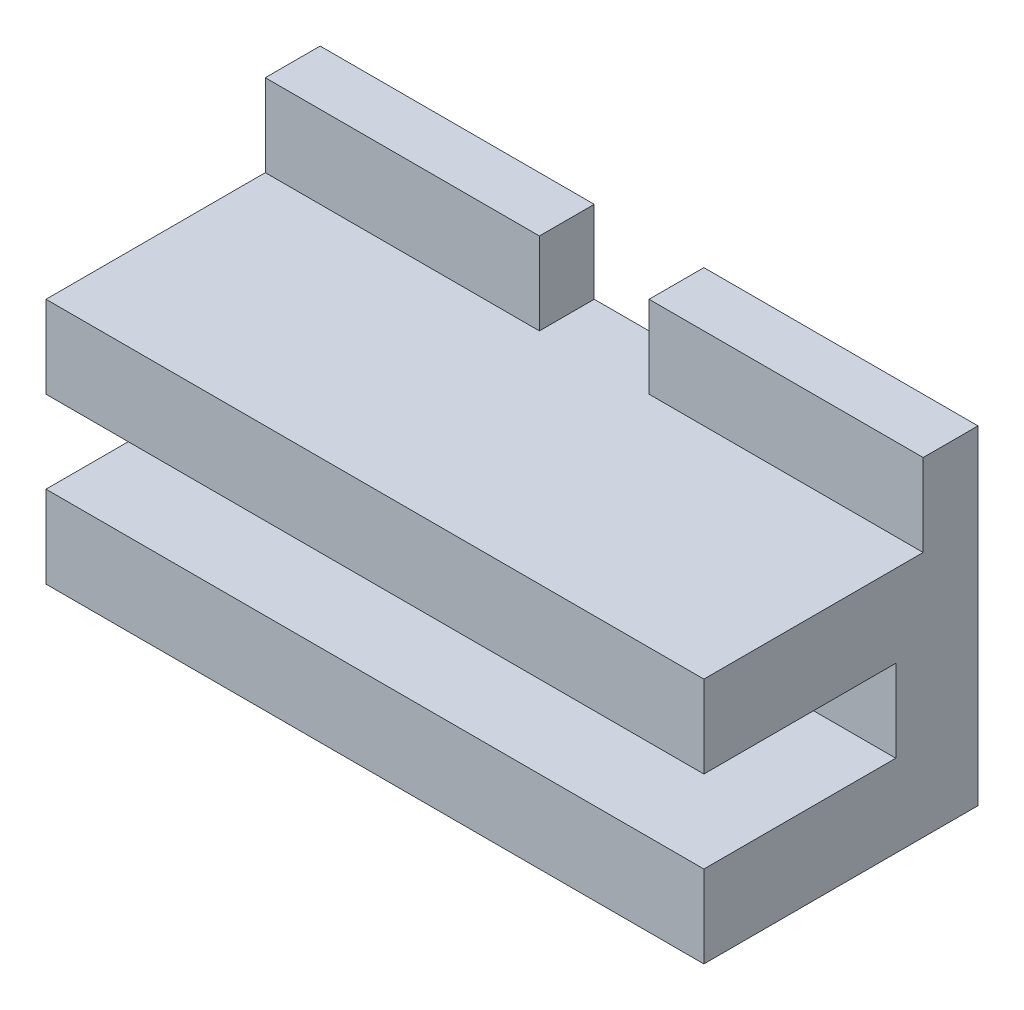
SolidWorks part; units mm, degrees
ref_plane "Front Plane" through (0, 0, 0) normal (0, 0, 1) x (1, 0, 0)
ref_plane "Top Plane" through (0, 0, 0) normal (0, 1, 0) x (1, 0, 0)
ref_plane "Right Plane" through (0, 0, 0) normal (1, 0, 0) x (0, 0, -1)
sketch "Sketch1" plane through (0, 0, 0) normal (0, 1, 0) x (1, 0, 0)
  line L1 (0, 0) -> (12, 0)
  line L2 (0, 0) -> (0, -5)
  line L3 (0, -5) -> (12, -5)
  line L4 (12, 0) -> (12, -5)
  dimension "D1" = 12
  dimension "D2" = 5
extrude "Boss-Extrude1" add sketch "Sketch1" along normal blind 4.5
sketch "Sketch2" plane through (0, 4.5, 0) normal (0, 1, 0) x (1, 0, 0)
  line L0 (0, 0) -> (0, -5) construction
  line L1 (0, -1.5) -> (12, -1.5)
  line L2 (0, -1.5) -> (0, -5)
  line L3 (0, -5) -> (12, -5)
  line L4 (12, -1.5) -> (12, -5)
  line L5 (12, 0) -> (0, 0) construction
  dimension "D1" = 1.5
extrude "Cut-Extrude1" cut sketch "Sketch2" against normal blind 1.5 from offset 1.5 offset against normal yes
sketch "Sketch4" plane through (0, 4.5, 0) normal (0, 1, 0) x (1, 0, 0)
  line L0 (12, -5) -> (12, 0) construction
  line L1 (0, 0) -> (5, 0)
  line L2 (0, 0) -> (0, -1)
  line L3 (0, -1) -> (5, -1)
  line L4 (12, 0) -> (12, -1)
  line L5 (7, -1) -> (12, -1)
  line L7 (5, 0) -> (5, -1)
  line L9 (7, 0) -> (7, -1)
  line L10 (7, 0) -> (12, 0)
  dimension "D1" = 1
  dimension "D2" = 2
extrude "Boss-Extrude2" add sketch "Sketch4" along normal blind 1.5
